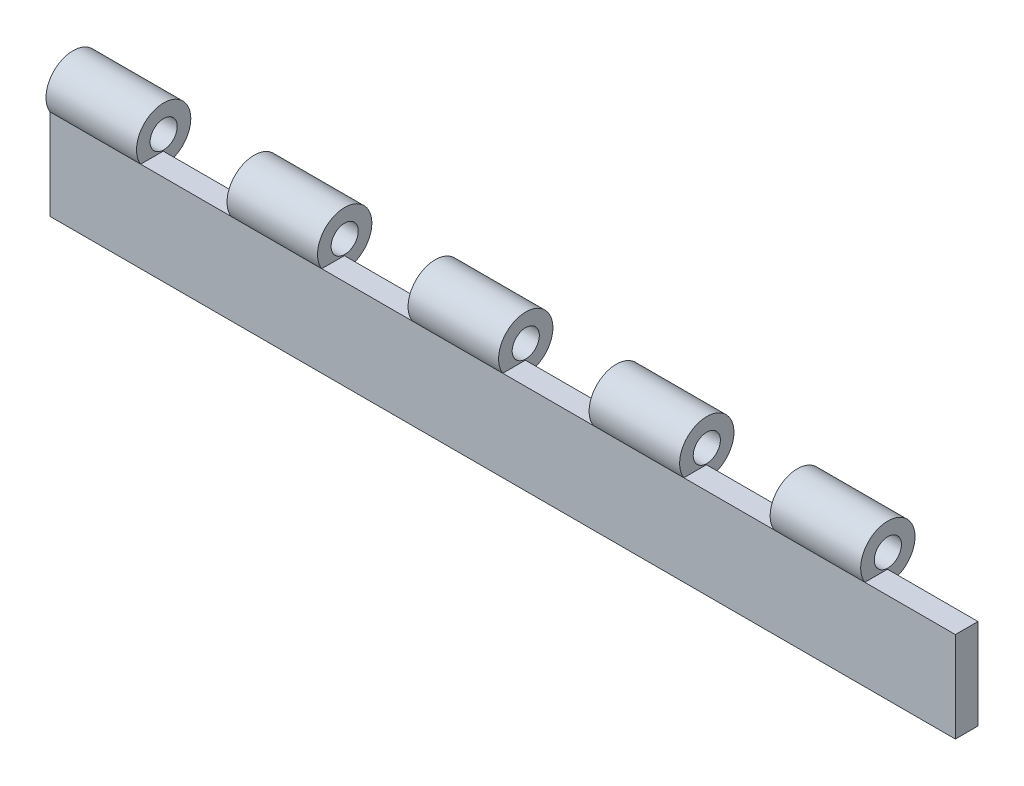
SolidWorks part; units mm, degrees
material "Acrylic (Medium-high impact)"
ref_plane "Front Plane" through (0, 0, 0) normal (0, 0, 1) x (1, 0, 0)
ref_plane "Top Plane" through (0, 0, 0) normal (0, 1, 0) x (1, 0, 0)
ref_plane "Right Plane" through (0, 0, 0) normal (1, 0, 0) x (0, 0, -1)
sketch "Sketch1" plane through (0, 0, 0) normal (0, 0, 1) x (1, 0, 0)
  line L1 (0, 0) -> (254, 0)
  line L2 (0, 0) -> (0, 25.4)
  line L3 (0, 25.4) -> (254, 25.4)
  line L4 (254, 0) -> (254, 25.4)
  dimension "D1" = 254
  dimension "D2" = 25.4
extrude "Boss-Extrude1" add sketch "Sketch1" along normal mid plane 6.35
sketch "Sketch2" plane through (0, 0, 0) normal (-1, 0, 0) x (0, 0, 1)
  circle A0 centre (-3.2773, 29.4536) radius 7.62
  circle A1 centre (-3.2773, 29.4536) radius 3.81
  point P1 (3.175, 71.12)
  point P5 (0, 70.4249)
  point P6 (0, 0)
  point P7 (-2.0582, 69.0388)
  point P8 (-3.6105, 66.9672)
  point P9 (0, 70.4194)
  point P10 (-3.3068, 67.5063)
  point P11 (-3.2773, 29.4536)
  dimension "D1" = 15.24
  dimension "D2" = 7.62
extrude "Boss-Extrude2" add sketch "Sketch2" against normal blind 25.4
pattern_linear "LPattern1" count 5 spacing 50.8 along (1, 0, 0) of "Boss-Extrude2"
scale "Scale1" bodies to scale 103 scale about centroid uniform scaling yes scale factor 0.9
